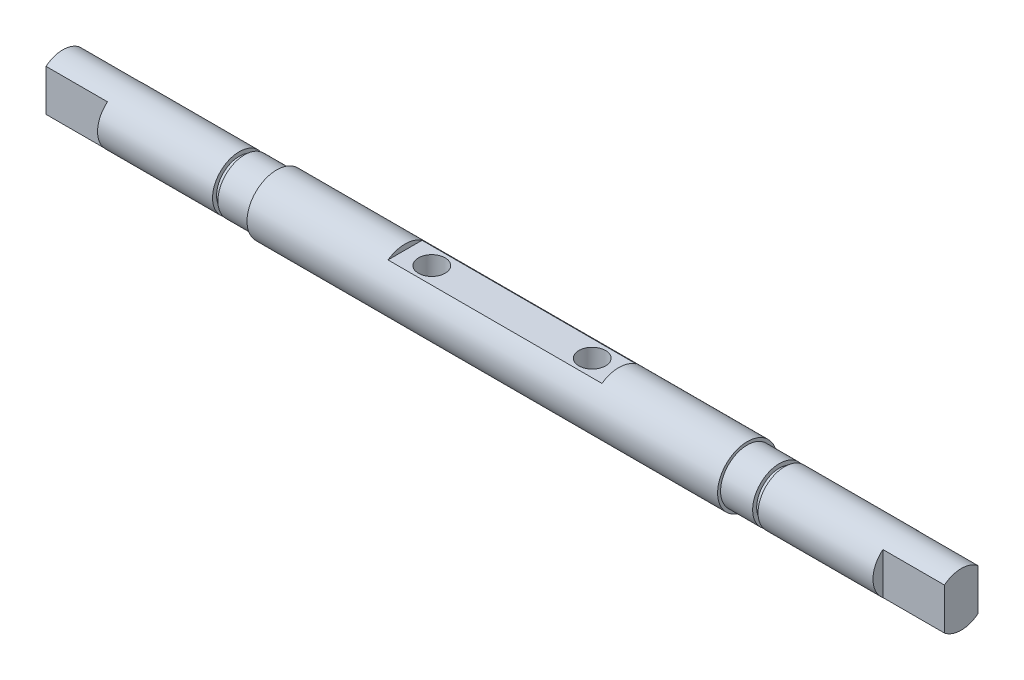
SolidWorks part; units mm, degrees
material "AISI 1020"
ref_plane "Alzado" through (0, 0, 0) normal (0, 0, 1) x (1, 0, 0)
ref_plane "Planta" through (0, 0, 0) normal (0, 1, 0) x (1, 0, 0)
ref_plane "Vista lateral" through (0, 0, 0) normal (1, 0, 0) x (0, 0, -1)
sketch "Croquis1" plane through (0, 0, 0) normal (0, 0, 1) x (1, 0, 0)
  line L0 (70.415, 0) -> (-86.7394, 0) construction
  line L1 (-19.4948, 11.1125) -> (68.5052, 11.1125)
  line L2 (-19.4948, 11.1125) -> (-19.4948, 10)
  line L3 (-19.4948, 10) -> (-31.4948, 10)
  line L4 (-99.4948, 10) -> (-99.4948, 0)
  line L5 (68.5052, 11.1125) -> (68.5052, 0)
  line L6 (68.5052, 0) -> (-99.4948, 0)
  line L7 (-33.4948, 10) -> (-99.4948, 10)
  line L8 (70.415, 0) -> (-148.7998, 0) construction
  line L9 (-33.4948, 10) -> (-33.4948, 8.5)
  line L10 (-33.4948, 8.5) -> (-31.4948, 8.5)
  line L11 (-31.4948, 10) -> (-31.4948, 8.5)
  dimension "D1" = 22.225
  dimension "D2" = 88
  dimension "D3" = 10
  dimension "D4" = 2
  dimension "D5" = 12
  dimension "D6" = 80
  dimension "D7" = 1.5
revolve "Revolución1" add sketch "Croquis1" angle 360 about L0
sketch "Croquis2" plane through (-99.4948, 0, 0) normal (-1, 0, 0) x (0, 0, 1)
  line L2 (-6.2784, -7.7835) -> (-6.2784, 7.7835)
  line L4 (6.2784, -7.7835) -> (6.2784, 7.7835)
  line L5 (-6.2784, -7.7835) -> (6.2784, 7.7835) construction
  line L6 (-6.2784, 7.7835) -> (6.2784, -7.7835) construction
  circle A0 centre (0, 0) radius 10 construction
  arc A1 (-6.2784, 7.7835) -> (-6.2784, -7.7835) centre (0, 0) ccw
  arc A2 (6.2784, -7.7835) -> (6.2784, 7.7835) centre (0, 0) ccw
  point P0 (0, 0)
  dimension "D1" = 12.5567
extrude "Cortar-Extruir1" cut sketch "Croquis2" against normal blind 23
mirror "Simetría2" about plane through (68.5052, 11.1125, 0) normal (1, 0, 0) of "Cortar-Extruir1", "Revolución1"
sketch "Croquis3" plane through (0, 0, 0) normal (0, 0, 1) x (1, 0, 0)
  line L0 (-19.4948, 11.1125) -> (-19.4948, 61.1125) construction
  line L1 (156.5052, 11.1125) -> (156.5052, 61.1125) construction
  line L4 (-19.4948, 61.1125) -> (156.5052, 61.1125) construction
  line L5 (-19.4948, 11.1125) -> (156.5052, 11.1125) construction
  line L6 (68.5052, 61.1125) -> (68.5052, 42.5998) construction
  line L7 (28.5052, 9.1125) -> (108.5052, 9.1125)
  line L8 (28.5052, 9.1125) -> (28.5052, 13.1125)
  line L9 (28.5052, 13.1125) -> (108.5052, 13.1125)
  line L10 (108.5052, 9.1125) -> (108.5052, 13.1125)
  line L11 (28.5052, 9.1125) -> (108.5052, 13.1125) construction
  line L12 (28.5052, 13.1125) -> (108.5052, 9.1125) construction
  line L13 (156.5052, 11.1125) -> (-19.4948, 11.1125) construction
  line L14 (-19.4948, -11.1125) -> (156.5052, -11.1125) construction
  line L16 (28.5052, -13.1125) -> (108.5052, -13.1125)
  line L17 (28.5052, -13.1125) -> (28.5052, -9.1125)
  line L18 (28.5052, -9.1125) -> (108.5052, -9.1125)
  line L19 (108.5052, -13.1125) -> (108.5052, -9.1125)
  line L20 (28.5052, -13.1125) -> (108.5052, -9.1125) construction
  line L21 (28.5052, -9.1125) -> (108.5052, -13.1125) construction
  point P5 (68.5052, 11.1125)
  point P16 (68.5052, -11.1125)
  dimension "D1" = 80
  dimension "D2" = 4
  dimension "D3" = 176
  dimension "D4" = 50
  dimension "D5" = 80
  dimension "D6" = 4
extrude "Cortar-Extruir2" cut sketch "Croquis3" against normal through all both and the other way through all
sketch "Croquis4" plane through (0, 9.1125, 0) normal (0, 1, 0) x (1, 0, 0)
  line L0 (28.5052, 6.36) -> (108.5052, 6.36) construction
  line L1 (28.5052, -6.36) -> (108.5052, -6.36) construction
  line L2 (108.5052, -6.36) -> (108.5052, 6.36) construction
  line L3 (28.5052, 6.36) -> (28.5052, -6.36) construction
  line L4 (28.5052, 0) -> (108.5052, 0) construction
  line L5 (68.5052, 6.36) -> (68.5052, 0) construction
  circle A0 centre (38.5052, 0) radius 5
  circle A1 centre (98.5052, 0) radius 5
  dimension "D2" = 10
  dimension "D3" = 30
  dimension "D4" = 30
  dimension "D1" = 80
extrude "Cortar-Extruir3" cut sketch "Croquis4" against normal through all
